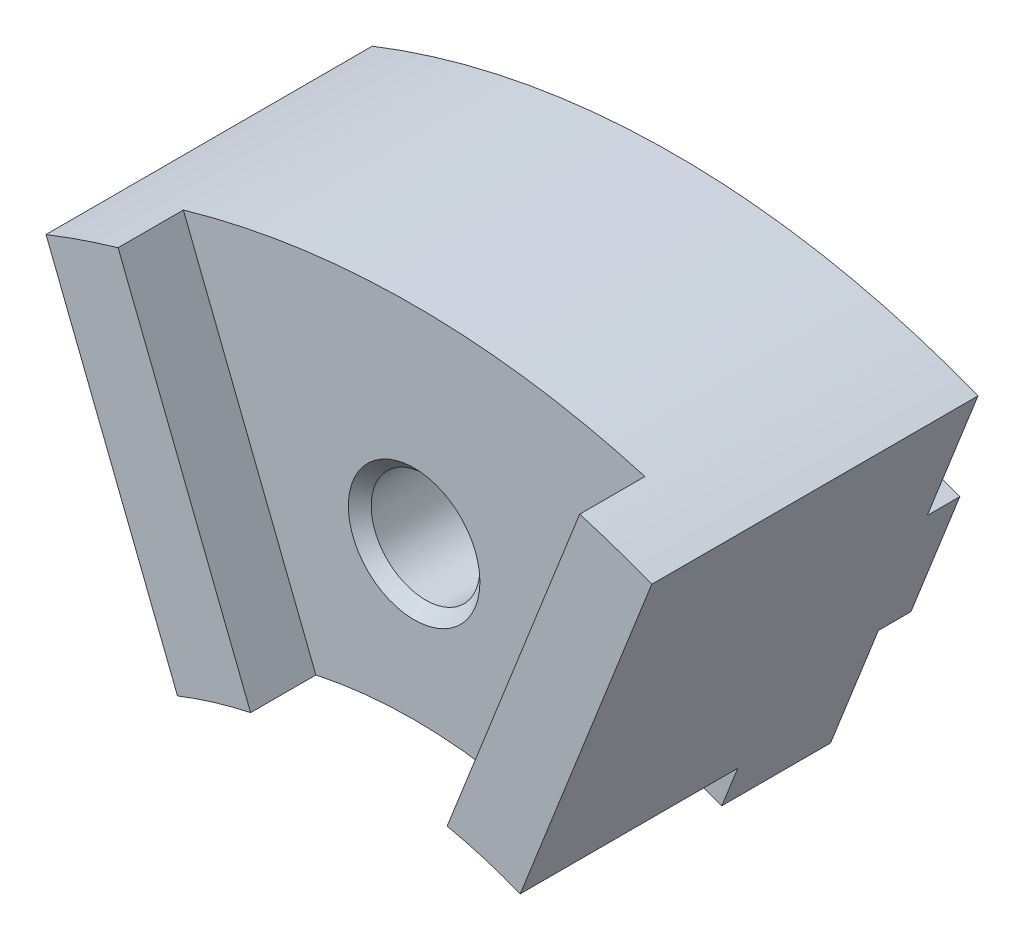
SolidWorks part; units mm, degrees
other "Caméra1"
ref_plane "Front Plane" through (0, 0, 0) normal (0, 0, 1) x (1, 0, 0)
ref_plane "Top Plane" through (0, 0, 0) normal (0, 1, 0) x (1, 0, 0)
ref_plane "Right Plane" through (0, 0, 0) normal (1, 0, 0) x (0, 0, -1)
sketch "Esquisse2" plane through (0, 0, 0) normal (0, 0, 1) x (1, 0, 0)
  line L0 (-7.1468, 18.1431) -> (-13.927, 35.3559)
  line L1 (0, 0) -> (0, 50.6285) construction
  line L2 (7.1468, 18.1431) -> (13.927, 35.3559)
  arc A0 (-13.927, 35.3559) -> (13.927, 35.3559) centre (0, 0) cw
  arc A1 (-7.1468, 18.1431) -> (7.1468, 18.1431) centre (0, 0) cw
  dimension "D1" = 38
  dimension "D2" = 19.5
  dimension "D3" = 43
extrude "Boss.-Extru.1" add sketch "Esquisse2" along normal blind 12
sketch "Esquisse4" plane through (0, 0, 12) normal (0, 0, 1) x (1, 0, 0)
  line L0 (-13.927, 35.3559) -> (-7.1468, 18.1431) construction
  line L1 (7.1468, 18.1431) -> (13.927, 35.3559) construction
  line L2 (-7.8798, 20.004) -> (-7.1468, 18.1431)
  line L3 (7.1468, 18.1431) -> (7.8798, 20.004)
  arc A0 (7.1468, 18.1431) -> (-7.1468, 18.1431) centre (0, 0) ccw construction
  arc A1 (7.1468, 18.1431) -> (-7.1468, 18.1431) centre (0, 0) ccw
  arc A2 (-7.8798, 20.004) -> (7.8798, 20.004) centre (0, 0) cw
  dimension "D1" = 21.5
extrude "Enlèv. mat.-Extru.1" cut sketch "Esquisse4" against normal blind 7
sketch "Esquisse5" plane through (0, 0, 12) normal (0, 0, 1) x (1, 0, 0)
  line L0 (-13.927, 35.3559) -> (-7.8798, 20.004) construction
  line L1 (7.8798, 20.004) -> (13.927, 35.3559) construction
  line L2 (-13.927, 35.3559) -> (-7.8798, 20.004)
  line L3 (7.8798, 20.004) -> (13.927, 35.3559)
  line L4 (-10.6114, 36.4883) -> (-4.5182, 21.0199)
  line L5 (-10.6706, 36.6386) -> (-4.6233, 21.2867) construction
  line L6 (4.5182, 21.0199) -> (10.6114, 36.4883)
  line L7 (4.6233, 21.2867) -> (10.6706, 36.6386) construction
  arc A0 (7.8798, 20.004) -> (-7.8798, 20.004) centre (0, 0) ccw construction
  arc A1 (13.927, 35.3559) -> (-13.927, 35.3559) centre (0, 0) ccw construction
  arc A2 (7.8798, 20.004) -> (4.5182, 21.0199) centre (0, 0) ccw
  arc A3 (13.927, 35.3559) -> (10.6114, 36.4883) centre (0, 0) ccw
  arc A4 (-10.6114, 36.4883) -> (-13.927, 35.3559) centre (0, 0) ccw
  arc A5 (-4.5182, 21.0199) -> (-7.8798, 20.004) centre (0, 0) ccw
  dimension "D1" = 3.5
  dimension "D2" = 3.5
extrude "Boss.-Extru.2" add sketch "Esquisse5" along normal blind 3
sketch "Esquisse6" plane through (0, 0, 0) normal (0, 0, -1) x (-1, 0, 0)
  line L0 (13.927, 35.3559) -> (7.1468, 18.1431) construction
  line L1 (-7.1468, 18.1431) -> (-13.927, 35.3559) construction
  line L2 (11.5913, 29.4263) -> (9.3458, 23.7256)
  line L3 (-9.3458, 23.7256) -> (-11.5913, 29.4263)
  line L4 (-4.0085, 25.183) -> (-6.2974, 30.9936)
  line L5 (6.2974, 30.9936) -> (4.0085, 25.183)
  line L7 (-7.1468, 18.1431) -> (-13.927, 35.3559) construction
  line L8 (-2.0295, 20.1589) -> (-8.8097, 37.3716) construction
  line L9 (8.8097, 37.3716) -> (2.0295, 20.1589) construction
  line L10 (13.927, 35.3559) -> (7.1468, 18.1431) construction
  arc A0 (-9.3458, 23.7256) -> (-4.0085, 25.183) centre (0, 0) cw
  arc A1 (-11.5913, 29.4263) -> (-6.2974, 30.9936) centre (0, 0) cw
  arc A2 (4.0085, 25.183) -> (9.3458, 23.7256) centre (0, 0) cw
  arc A3 (6.2974, 30.9936) -> (11.5913, 29.4263) centre (0, 0) cw
  dimension "D1" = 25.5
  dimension "D2" = 31.6269
  dimension "D3" = 5.5
  dimension "D4" = 5.5
extrude "Boss.-Extru.3" add sketch "Esquisse6" along normal blind 1.5
hole_wizard "Trou taraudé M61" positions "Esquisse7" profile "Esquisse8" tap size "M6" standard "ISO" end condition through all
sketch "Esquisse7" plane through (0, 0, 12) normal (0, 0, 1) x (1, 0, 0)
  point P0 (0, 28.5)
  dimension "D1" = 28.5
sketch "Esquisse8" plane through (0, 28.5, 12) normal (1, 0, 0) x (0, -1, 0)
  line L0 (0, 0) -> (0, 13.5)
  line L1 (0, 13.5) -> (2.5, 13.5)
  line L2 (2.5, 13.5) -> (2.5, 0.525)
  line L3 (2.5, 0.525) -> (3.025, 0)
  line L5 (3.025, 0) -> (0, 0)
  line L6 (-2.5, 0.525) -> (-3.025, 0) construction
  line L11 (0, -6.35) -> (0, 107.95) construction
  dimension "Diamètre du trou pour taraudage jusqu'au prochain" = 5
  dimension "Profondeur du trou pour taraudage jusqu'au prochain" = 13.5
  dimension "Diamètre du fraisage entrant" = 6.05
  dimension "Angle du fraisage entrant" = 90
cosmetic thread "Filetage de perçage1" parameters "D2"=6
